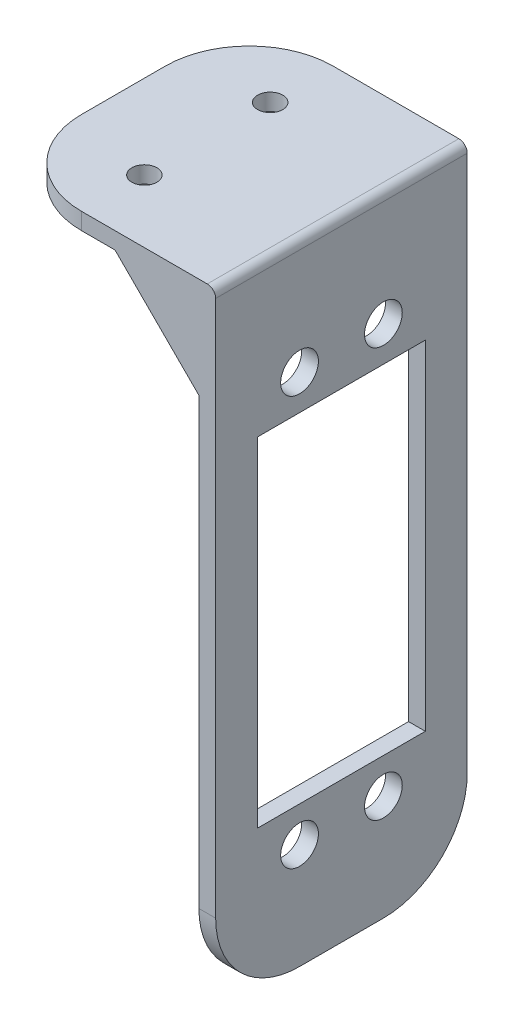
SolidWorks part; units mm, degrees
ref_plane "Front Plane" through (0, 0, 0) normal (0, 0, 1) x (1, 0, 0)
ref_plane "Top Plane" through (0, 0, 0) normal (0, 1, 0) x (1, 0, 0)
ref_plane "Right Plane" through (0, 0, 0) normal (1, 0, 0) x (0, 0, -1)
sketch "Sketch1" plane through (0, 0, 0) normal (0, 1, 0) x (1, 0, 0)
  line L1 (0, 0) -> (25, 0)
  line L2 (0, 0) -> (0, 30)
  line L3 (0, 30) -> (25, 30)
  line L4 (25, 0) -> (25, 30)
  circle A1 centre (10, 22.5) radius 1.5
  circle A2 centre (10, 7.5) radius 1.5
  dimension "D3" = 3
  dimension "D4" = 7.5
  dimension "D5" = 15
  dimension "D6" = 7.5
  dimension "D7" = 15
  dimension "D1" = 30
  dimension "D2" = 25
extrude "Boss-Extrude1" add sketch "Sketch1" along normal blind 2
sketch "Sketch2" plane through (0, 2, 0) normal (0, 1, 0) x (1, 0, 0)
  line L0 (0, 0) -> (25, 0) construction
  line L1 (25, 30) -> (24, 30)
  line L3 (25, 0) -> (24, 0)
  line L4 (24, 30) -> (24, 0)
  line L6 (25, 30) -> (26, 30)
  line L8 (25, 0) -> (26, 0)
  line L9 (26, 30) -> (26, 0)
  dimension "D1" = 1
  dimension "D2" = 1
extrude "Boss-Extrude2" add sketch "Sketch2" against normal blind 75
fillet "Fillet1" radius 1 2 edges at (24, 0, -15) (26, 2, -15)
sketch "Sketch3" plane through (24, 0, 0) normal (-1, 0, 0) x (0, 0, 1)
  line L0 (-15, -9) -> (-14.5, -9)
  line L1 (-15, -9) -> (-15, -15.8)
  line L2 (-15, -15.8) -> (-14.5, -15.8)
  line L3 (-14.5, -9) -> (-14.5, -15.8)
  line L4 (-15, -9) -> (-15.5, -9)
  line L5 (-15, -9) -> (-15, -15.8)
  line L6 (-15, -15.8) -> (-15.5, -15.8)
  line L7 (-15.5, -9) -> (-15.5, -15.8)
  line L8 (-15, -15.8) -> (-5, -15.8)
  line L9 (-15, -15.8) -> (-15, -56.2)
  line L10 (-15, -56.2) -> (-5, -56.2)
  line L11 (-5, -15.8) -> (-5, -56.2)
  line L12 (-15, -15.8) -> (-25, -15.8)
  line L13 (-15, -15.8) -> (-15, -56.2)
  line L14 (-15, -56.2) -> (-25, -56.2)
  line L15 (-25, -15.8) -> (-25, -56.2)
  line L16 (-15, -56.2) -> (-14.5, -56.2)
  line L17 (-15, -56.2) -> (-15, -63)
  line L18 (-15, -63) -> (-14.5, -63)
  line L19 (-14.5, -56.2) -> (-14.5, -63)
  line L20 (-15, -56.2) -> (-15.5, -56.2)
  line L21 (-15, -56.2) -> (-15, -63)
  line L22 (-15, -63) -> (-15.5, -63)
  line L23 (-15.5, -56.2) -> (-15.5, -63)
  line L24 (-30, -73) -> (0, -73) construction
  line L26 (0, -73) -> (0, -1) construction
  line L27 (-30, -73) -> (-30, 1) construction
  circle A0 centre (-20, -11.6) radius 2.25
  circle A1 centre (-10, -11.6) radius 2.25
  circle A2 centre (-10, -60.4) radius 2.25
  circle A3 centre (-20, -60.4) radius 2.25
  dimension "D19" = 10
  dimension "D1" = 0.5
  dimension "D2" = 0.5
  dimension "D3" = 6.8
  dimension "D4" = 40.4
  dimension "D5" = 10
  dimension "D6" = 10
  dimension "D7" = 4.5
  dimension "D8" = 4.2
  dimension "D9" = 4.5
  dimension "D10" = 4.2
  dimension "D11" = 0.5
  dimension "D12" = 0.5
  dimension "D13" = 6.8
  dimension "D14" = 4.2
  dimension "D15" = 4.5
  dimension "D16" = 4.5
  dimension "D17" = 4.2
  dimension "D18" = 10
  dimension "D20" = 5
extrude "Cut-Extrude1" cut sketch "Sketch3" against normal blind 75 contours A3 | L12 L15 L14 L9 L6 | A2 | L14 L23 L22 L17 | L19 L10 L17 L18 | L11 L8 L2 L9 L10 | A1 | A0 | L4 L7 L6 L1 | L3 L0 L1 L2
sketch "Sketch4" plane through (26, 0, 0) normal (1, 0, 0) x (0, 0, -1)
  line L0 (30, -73) -> (30, 1) construction
  line L1 (30, -56.2) -> (0, -56.2)
  line L2 (30, -56.2) -> (30, -15.8)
  line L3 (30, -15.8) -> (0, -15.8)
  line L4 (0, -56.2) -> (0, -15.8)
  dimension "D1" = 30
  dimension "D2" = 40.4
sketch "Sketch5" plane through (26, 0, 0) normal (1, 0, 0) x (0, 0, -1)
  line L1 (15.5, -9) -> (14.5, -9)
  line L2 (15.5, -9) -> (15.5, -15.8)
  line L3 (15.5, -15.8) -> (14.5, -15.8)
  line L4 (14.5, -9) -> (14.5, -15.8)
  line L5 (15.5, -63) -> (14.5, -63)
  line L6 (15.5, -63) -> (15.5, -56.2)
  line L7 (15.5, -56.2) -> (14.5, -56.2)
  line L8 (14.5, -63) -> (14.5, -56.2)
extrude "Boss-Extrude3" add sketch "Sketch5" against normal blind 2
fillet "Fillet2" radius 10 4 edges at (25, -73, -30) (25, -73, 0) (0, 1, 0) (0, 1, -30)
ref_plane "Plane1" through (0, 0, -15) normal (0, 0, 1) x (1, 0, 0)
sketch "Sketch8" plane through (0, 0, 0) normal (0, 0, 1) x (1, 0, 0)
  line L0 (10, 0) -> (23, 0) construction
  line L1 (14, 0) -> (24, 0)
  line L2 (14, 0) -> (14, -10)
  line L3 (14, -10) -> (24, -10)
  line L4 (24, 0) -> (24, -10)
  line L5 (24, -63) -> (24, -1) construction
  line L6 (14, 0) -> (24, -10)
  circle A0 centre (23, -1) radius 1
  dimension "D1" = 10
  dimension "D2" = 10
extrude "Boss-Extrude4" add sketch "Sketch8" against normal blind 2 contours A0 L1 L6 L4 | A0
mirror "Mirror1" about plane through (0, 0, -15) normal (0, 0, 1) of "Boss-Extrude4"
